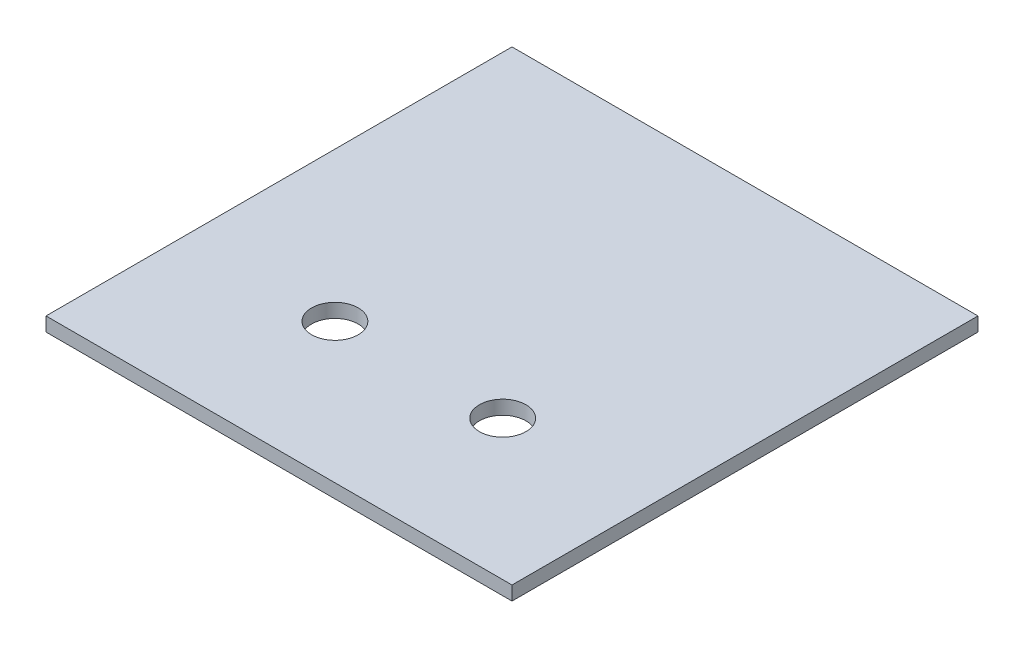
SolidWorks part; units mm, degrees
ref_plane "Front" through (0, 0, 0) normal (0, 0, 1) x (1, 0, 0)
ref_plane "Top" through (0, 0, 0) normal (0, 1, 0) x (1, 0, 0)
ref_plane "Right" through (0, 0, 0) normal (1, 0, 0) x (0, 0, -1)
sketch "草图1" plane through (0, 0, 0) normal (0, 1, 0) x (1, 0, 0)
  line L1 (-25, -25) -> (25, -25)
  line L2 (-25, -25) -> (-25, 25)
  line L3 (-25, 25) -> (25, 25)
  line L4 (25, -25) -> (25, 25)
  line L5 (-25, -25) -> (25, 25) construction
  line L6 (-25, 25) -> (25, -25) construction
  point P0 (0, 0)
extrude "凸台-拉伸1" add sketch "草图1" along normal blind 1.5
sketch "草图2" plane through (0, 1.5, 0) normal (0, 1, 0) x (1, 0, 0)
  circle A0 centre (9, -10) radius 2.5
extrude "切除-拉伸1" cut sketch "草图2" against normal through all
mirror "镜向1" about plane through (0, 0, 0) normal (1, 0, 0) of "切除-拉伸1"
